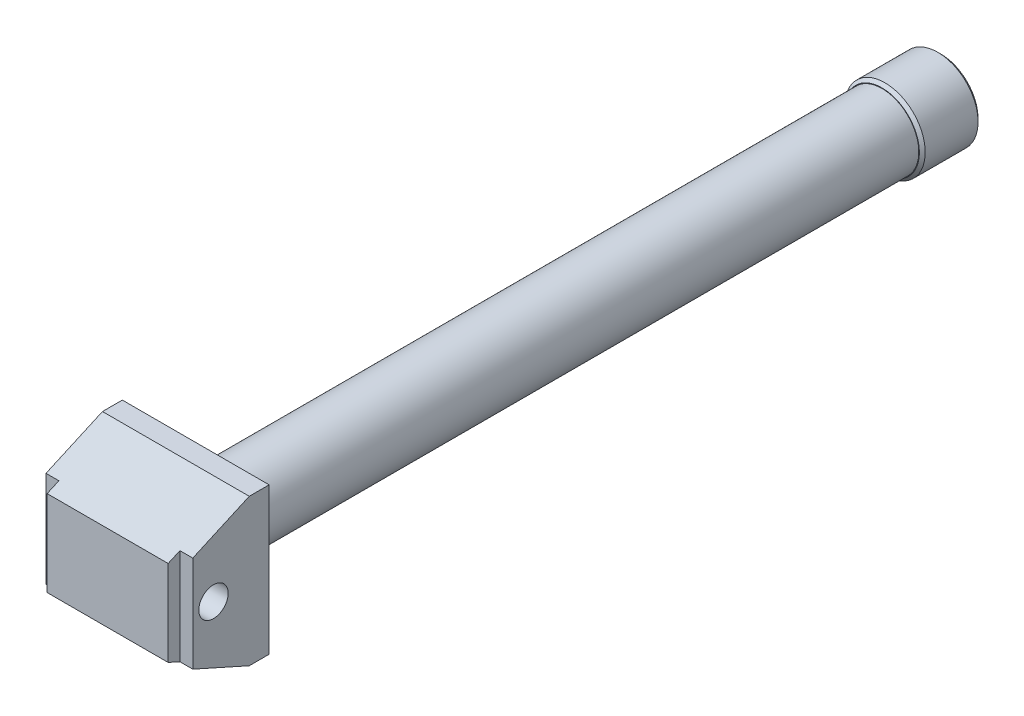
SolidWorks part; units mm, degrees
ref_plane "Front Plane" through (0, 0, 0) normal (0, 0, 1) x (1, 0, 0)
ref_plane "Top Plane" through (0, 0, 0) normal (0, 1, 0) x (1, 0, 0)
ref_plane "Right Plane" through (0, 0, 0) normal (1, 0, 0) x (0, 0, -1)
sketch "Sketch1" plane through (0, 0, 0) normal (0, 0, 1) x (1, 0, 0)
  line L1 (-125, -125) -> (125, -125)
  line L2 (-125, -125) -> (-125, 125)
  line L3 (-125, 125) -> (125, 125)
  line L4 (125, -125) -> (125, 125)
  line L5 (-125, -125) -> (125, 125) construction
  line L6 (-125, 125) -> (125, -125) construction
  point P0 (0, 0)
  dimension "D1" = 250
  dimension "D2" = 250
extrude "Boss-Extrude1" add sketch "Sketch1" along normal blind 150
sketch "Sketch2" plane through (0, 0, 0) normal (0, 0, -1) x (-1, 0, 0)
  circle A0 centre (0, 0) radius 62.5
  dimension "D1" = 125
extrude "Boss-Extrude2" add sketch "Sketch2" along normal blind 1269
sketch "Sketch3" plane through (-125, 0, 0) normal (-1, 0, 0) x (0, 0, 1)
  line L0 (150, 125) -> (150, -125) construction
  line L1 (0, 0) -> (150, 0) construction
  line L2 (33.82, -125) -> (150, -125)
  line L3 (150, -125) -> (0, -125) construction
  line L4 (150, -125) -> (150, -73)
  line L5 (150, -73) -> (33.82, -125)
  line L6 (150, 125) -> (150, 73)
  line L7 (33.82, 125) -> (150, 125)
  line L8 (150, 73) -> (33.82, 125)
  circle A0 centre (94.75, 0) radius 25
  dimension "D1" = 50
  dimension "D2" = 55.25
  dimension "D3" = 116.18
  dimension "D4" = 52
extrude "Cut-Extrude1" cut sketch "Sketch3" against normal blind 1269
sketch "Sketch4" plane through (0, 0, -1269) normal (0, 0, -1) x (-1, 0, 0)
  circle A0 centre (0, 0) radius 37.5
  dimension "D1" = 75
extrude "Cut-Extrude2" cut sketch "Sketch4" against normal up to surface (1269 mm away) up to face at (-62.5, 0, 0)
sketch "Sketch5" plane through (0, 0, 150) normal (0, 0, 1) x (1, 0, 0)
  line L0 (-125, 73) -> (-125, -73) construction
  line L1 (-223.0687, 191.2187) -> (-103.06, 191.2187)
  line L2 (-223.0687, 191.2187) -> (-223.0687, -159.4092)
  line L3 (-223.0687, -159.4092) -> (-103.06, -159.4092)
  line L4 (-103.06, 191.2187) -> (-103.06, -159.4092)
  line L5 (103.06, -159.4092) -> (202.1033, -159.4092)
  line L6 (103.06, -159.4092) -> (103.06, 191.2187)
  line L7 (103.06, 191.2187) -> (202.1033, 191.2187)
  line L8 (202.1033, -159.4092) -> (202.1033, 191.2187)
  line L9 (125, -73) -> (125, 73) construction
  dimension "D1" = 21.94
  dimension "D2" = 21.94
extrude "Cut-Extrude3" cut sketch "Sketch5" against normal blind 20 contours L2 L1 L4 L3 | L6 L5 L8 L7
sketch "Sketch6" plane through (0, 0, -1269) normal (0, 0, -1) x (-1, 0, 0)
  circle A0 centre (0, 0) radius 68.445
  circle A3 centre (0, 0) radius 62.5
  circle A4 centre (0, 0) radius 62.5
  dimension "D1" = 136.89
  dimension "D2" = 0
extrude "Boss-Extrude3" add sketch "Sketch6" against normal blind 100 separate body
chamfer "Chamfer1" distance 5 angle 45 2 edges at (-68.445, 0, -1169) (-68.445, 0, -1269)
chamfer "Chamfer2" distance 5 angle 45 1 edges at (-37.5, 0, -1269)
